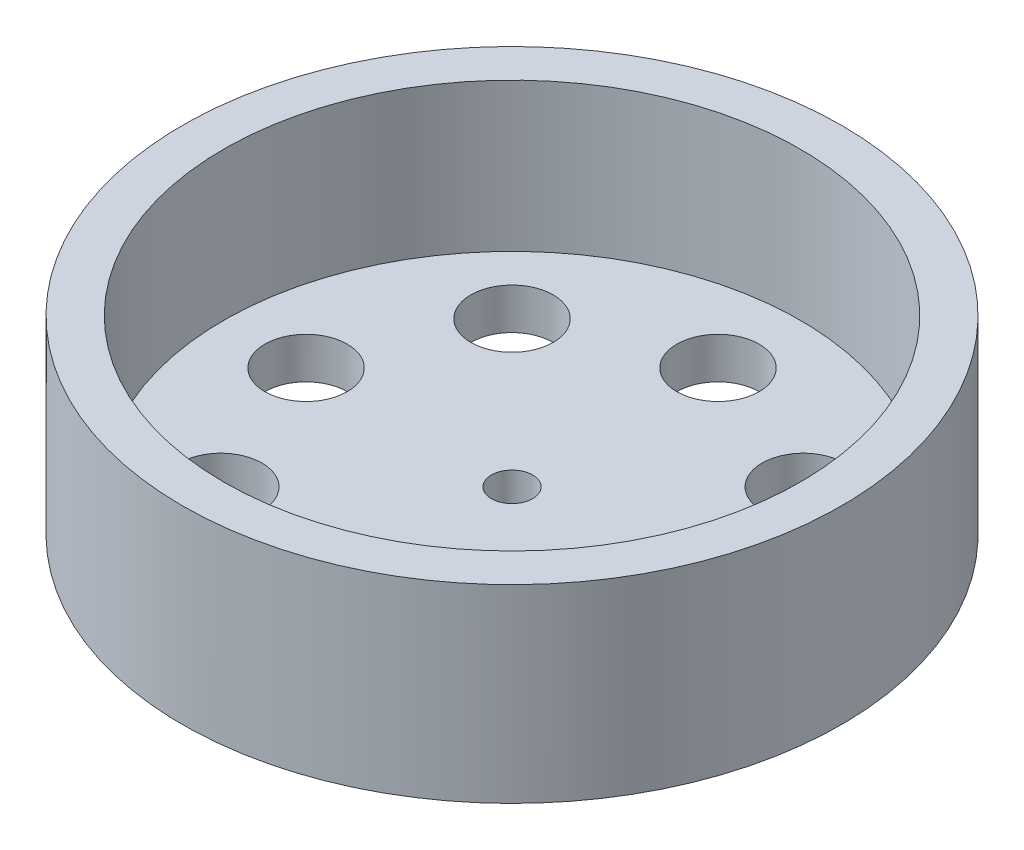
SolidWorks part; units mm, degrees
ref_plane "Plan de face" through (0, 0, 0) normal (0, 0, 1) x (1, 0, 0)
ref_plane "Plan de dessus" through (0, 0, 0) normal (0, 1, 0) x (1, 0, 0)
ref_plane "Plan de droite" through (0, 0, 0) normal (1, 0, 0) x (0, 0, -1)
sketch "Esquisse1" plane through (0, 0, 0) normal (0, 1, 0) x (1, 0, 0)
  circle A0 centre (0, 0) radius 40
extrude "Boss.-Extru.2" add sketch "Esquisse1" along normal blind 35
sketch "Esquisse4" plane through (0, 35, 0) normal (0, 1, 0) x (1, 0, 0)
  circle A0 centre (0, 0) radius 35
extrude "Enlèv. mat.-Extru.2" cut sketch "Esquisse4" against normal blind 18
sketch "Esquisse5" plane through (0, 0, 0) normal (0, -1, 0) x (-1, 0, 0)
  circle A0 centre (0, 0) radius 40
sketch "Esquisse6" plane through (0, 17, 0) normal (0, 1, 0) x (1, 0, 0)
  circle A0 centre (0, 0) radius 2.5
extrude "Enlèv. mat.-Extru.4" cut sketch "Esquisse6" against normal blind 12
extrude "Enlèv. mat.-Extru.5" cut sketch "Esquisse5" against normal blind 12
sketch "Esquisse7" plane through (0, 12, 0) normal (0, -1, 0) x (1, 0, 0)
  circle A0 centre (-25, 0) radius 5
  circle A1 centre (-17.6777, 17.6777) radius 5
  circle A2 centre (0, 25) radius 5
  circle A3 centre (17.6777, 17.6777) radius 5
  circle A4 centre (25, 0) radius 5
  circle A5 centre (17.6777, -17.6777) radius 5
  circle A6 centre (0, -25) radius 5
  circle A7 centre (-17.6777, -17.6777) radius 5
  point P19 (0, 0)
  dimension "D1" = 8
extrude "Enlèv. mat.-Extru.7" cut sketch "Esquisse7" against normal blind 10
